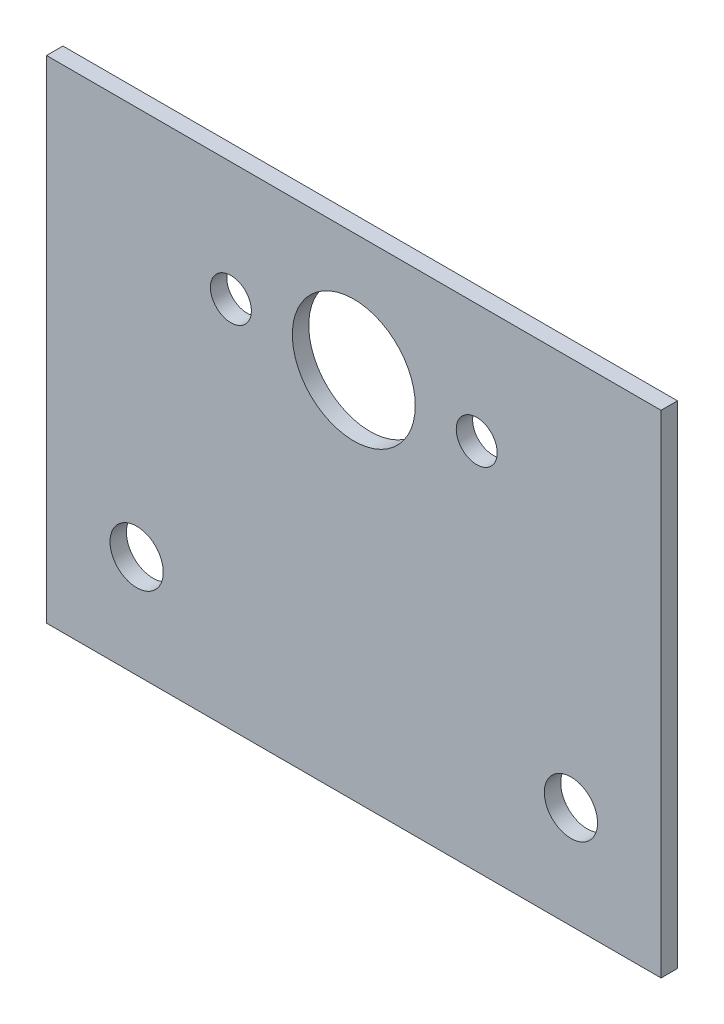
SolidWorks part; units mm, degrees
ref_plane "Front Plane" through (0, 0, 0) normal (0, 0, 1) x (1, 0, 0)
ref_plane "Top Plane" through (0, 0, 0) normal (0, 1, 0) x (1, 0, 0)
ref_plane "Right Plane" through (0, 0, 0) normal (1, 0, 0) x (0, 0, -1)
sketch "Sketch2" plane through (0, 0, 0) normal (0, 0, 1) x (1, 0, 0)
  line L0 (37.5, 0) -> (37.5, 45.5) construction
  line L1 (0, 0) -> (75, 0)
  line L2 (0, 0) -> (0, 60)
  line L3 (0, 60) -> (75, 60)
  line L4 (75, 0) -> (75, 60)
  line L5 (37.5, 45.5) -> (0, 45.5) construction
  circle A0 centre (37.5, 45.5) radius 7.5
  circle A1 centre (64, 12.5) radius 3.25
  circle A2 centre (11, 12.5) radius 3.25
  circle A3 centre (22.5, 45.5) radius 2.5
  circle A5 centre (52.5, 45.5) radius 2.5
  point P17 (0, 0)
  dimension "D1" = 15
  dimension "D3" = 6.5
  dimension "D4" = 11
  dimension "D5" = 12.5
  dimension "D8" = 5
  dimension "D10" = 15
  dimension "D2" = 45.5
  dimension "D6" = 75
  dimension "D7" = 60
extrude "Boss-Extrude1" add sketch "Sketch2" along normal blind 2
